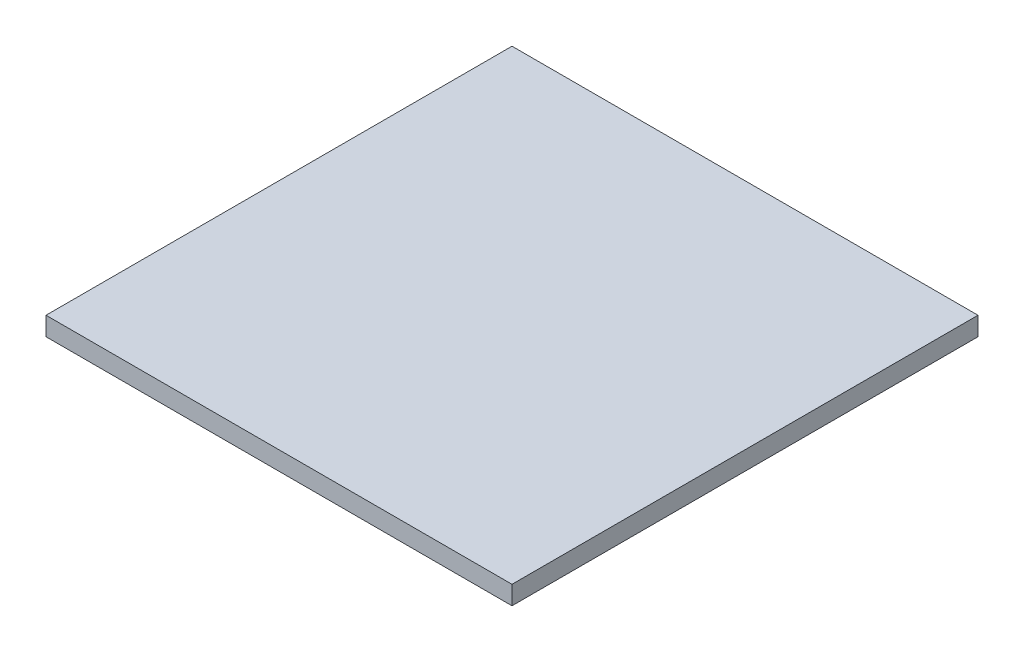
SolidWorks part; units mm, degrees
material "PE High Density"
ref_plane "Front Plane" through (0, 0, 0) normal (0, 0, 1) x (1, 0, 0)
ref_plane "Top Plane" through (0, 0, 0) normal (0, 1, 0) x (1, 0, 0)
ref_plane "Right Plane" through (0, 0, 0) normal (1, 0, 0) x (0, 0, -1)
sketch "Sketch1" plane through (0, 0, 0) normal (0, 1, 0) x (1, 0, 0)
  line L0 (-250, 250) -> (250, 250)
  line L1 (-250, 250) -> (-250, -250)
  line L2 (250, 250) -> (250, -250)
  line L3 (-250, -250) -> (250, -250)
  line L4 (-250, 250) -> (250, -250) construction
  line L5 (250, 250) -> (-250, -250) construction
  point P1 (0, 0)
  dimension "D1" = 500
  dimension "D2" = 500
extrude "Boss-Extrude1" add sketch "Sketch1" along normal blind 20
